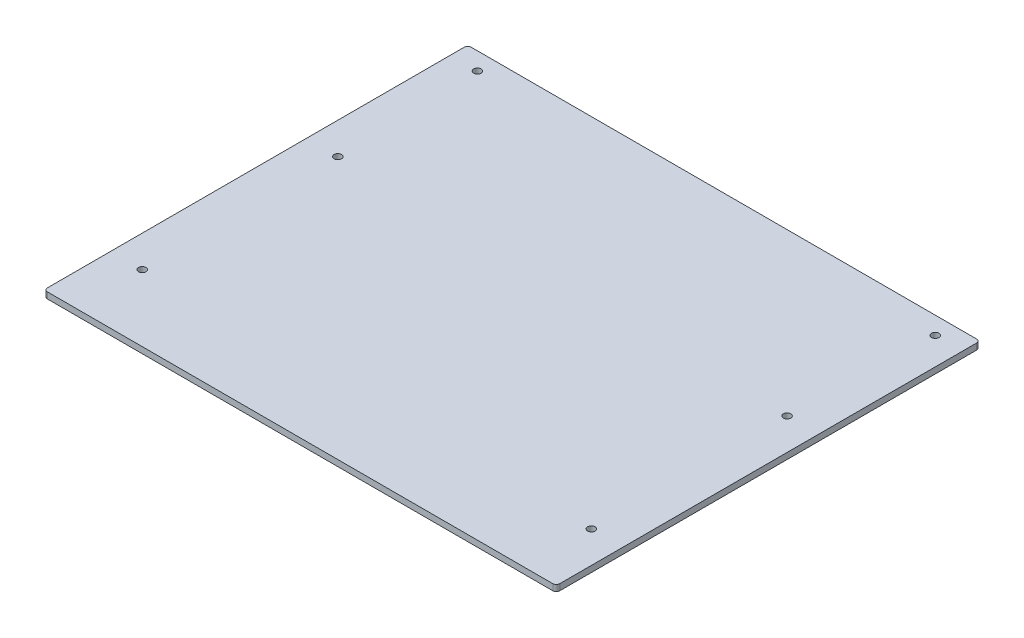
SolidWorks part; units mm, degrees
material "ABS PC"
ref_plane "Front Plane" through (0, 0, 0) normal (0, 0, 1) x (1, 0, 0)
ref_plane "Top Plane" through (0, 0, 0) normal (0, 1, 0) x (1, 0, 0)
ref_plane "Right Plane" through (0, 0, 0) normal (1, 0, 0) x (0, 0, -1)
sketch "Sketch1" plane through (0, 0, 0) normal (0, 1, 0) x (1, 0, 0)
  line L0 (231.775, 383.413) -> (231.775, 0) construction
  line L1 (0, 0) -> (463.55, 0)
  line L2 (0, 0) -> (0, 383.413)
  line L3 (0, 383.413) -> (463.55, 383.413)
  line L4 (463.55, 0) -> (463.55, 383.413)
  line L5 (28.575, 60.325) -> (28.575, 237.363) construction
  line L6 (28.575, 237.363) -> (28.575, 414.401) construction
  line L7 (434.975, 237.363) -> (434.975, 414.401) construction
  line L8 (434.975, 60.325) -> (434.975, 237.363) construction
  circle A0 centre (28.575, 60.325) radius 3.3782
  circle A1 centre (28.575, 237.363) radius 3.3782
  circle A4 centre (434.975, 237.363) radius 3.3782
  circle A5 centre (434.975, 60.325) radius 3.3782
  dimension "D3" = 6.7564
  dimension "D1" = 463.55
  dimension "D2" = 146.05
  dimension "D4" = 60.325
  dimension "D5" = 28.575
  dimension "D6" = 177.038
extrude "Boss-Extrude1" add sketch "Sketch1" along normal blind 5.588
fillet "Fillet1" radius 3.175 4 edges at (0, 2.794, -383.413) (463.55, 2.794, -383.413) (0, 2.794, 0) (463.55, 2.794, 0)
sketch "Sketch2" plane through (0, 5.588, 0) normal (0, 1, 0) x (1, 0, 0)
  line L0 (0, 367.538) -> (24.638, 367.538) construction
  line L1 (0, 380.238) -> (0, 3.175) construction
  line L2 (24.638, 367.538) -> (24.638, 383.413) construction
  line L3 (460.375, 383.413) -> (3.175, 383.413) construction
  line L4 (231.775, 383.413) -> (231.775, 0) construction
  line L5 (3.175, 0) -> (460.375, 0) construction
  line L6 (438.912, 367.538) -> (438.912, 383.413) construction
  line L7 (463.55, 367.538) -> (438.912, 367.538) construction
  circle A0 centre (24.638, 367.538) radius 3.3782
  circle A1 centre (438.912, 367.538) radius 3.3782
  dimension "D3" = 6.7564
  dimension "D1" = 15.875
  dimension "D2" = 24.638
extrude "Cut-Extrude1" cut sketch "Sketch2" against normal through all
